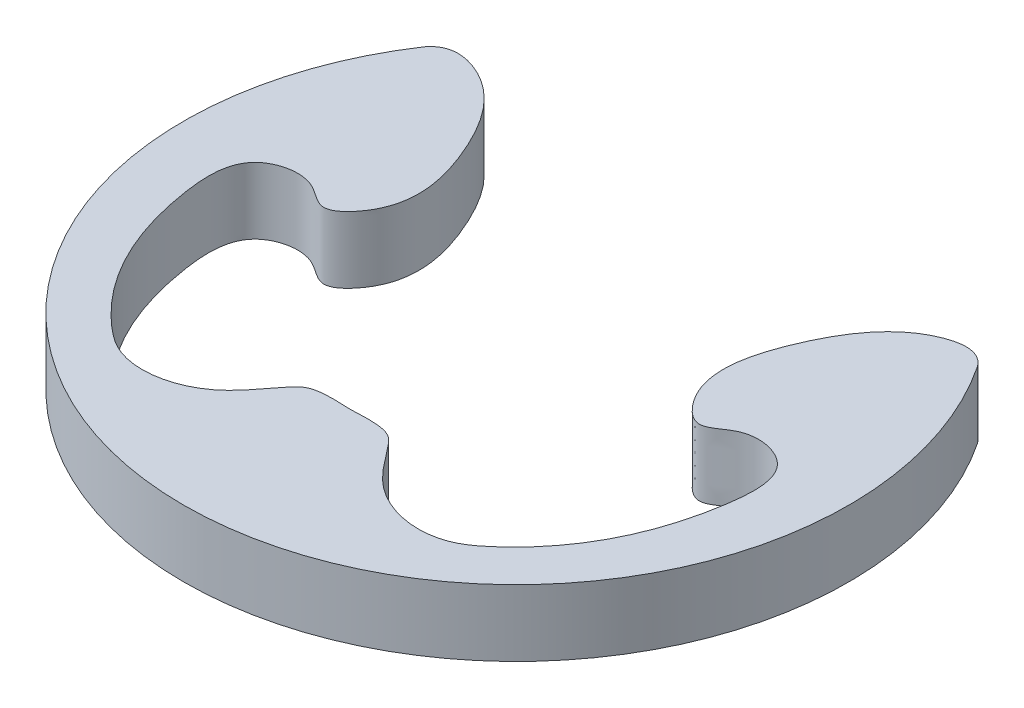
SolidWorks part; units mm, degrees
ref_plane "Front Plane" through (0, 0, 0) normal (0, 0, 1) x (1, 0, 0)
ref_plane "Top Plane" through (0, 0, 0) normal (0, 1, 0) x (1, 0, 0)
ref_plane "Right Plane" through (0, 0, 0) normal (1, 0, 0) x (0, 0, -1)
sketch "Sketch1" plane through (0, 0, 0) normal (0, 1, 0) x (1, 0, 0)
  circle A0 centre (0, 0) radius 2
  dimension "D1" = 4
extrude "Boss-Extrude1" add sketch "Sketch1" along normal blind 0.4
sketch "Sketch2" plane through (0, 0.4, 0) normal (0, 1, 0) x (1, 0, 0)
  line L0 (0, 2) -> (0, -2) construction
  circle A0 centre (0, 0) radius 2 construction
  circle A1 centre (0, 0) radius 1
  circle A2 centre (0, 0) radius 2
  spline S0 degree 3 poles (0, -1) (0.2083, -0.9882) (0.2857, -1.0252) (0.5161, -1.395) (0.9193, -1.4671) (1.3833, -1.1055) (1.6235, -0.6357) (1.6609, 0.031) (1.3057, 0.1106) (1.1336, -0.0762) (0.849, 0.1924) (0.9658, 0.7035) (1.2697, 1.1616) (1.6126, 1.2021) (1.6793, 1.0863) knots 0 0 0 0 0.062886 0.124136 0.231355 0.267285 0.479704 0.55555 0.615511 0.65108 0.684138 0.810147 0.937554 1 1 1 1
  spline S1 degree 3 poles (0, -1) (-0.2083, -0.9882) (-0.2857, -1.0252) (-0.5161, -1.395) (-0.9193, -1.4671) (-1.3833, -1.1055) (-1.6235, -0.6357) (-1.6609, 0.031) (-1.3057, 0.1106) (-1.1336, -0.0762) (-0.849, 0.1924) (-0.9658, 0.7035) (-1.2697, 1.1616) (-1.6126, 1.2021) (-1.6793, 1.0863) knots 0 0 0 0 0.062886 0.124136 0.231355 0.267285 0.479704 0.55555 0.615511 0.65108 0.684138 0.810147 0.937554 1 1 1 1
  circle M2 centre (0, 0) radius 2
  dimension "D1" = 2
extrude "Cut-Extrude1" cut sketch "Sketch2" against normal up to next contours L0 S1 A1 M2 | A2 L0 A1 S0 | A1 L0 S0 | A1 S0 | L0 A1 S1 | S1 A1
